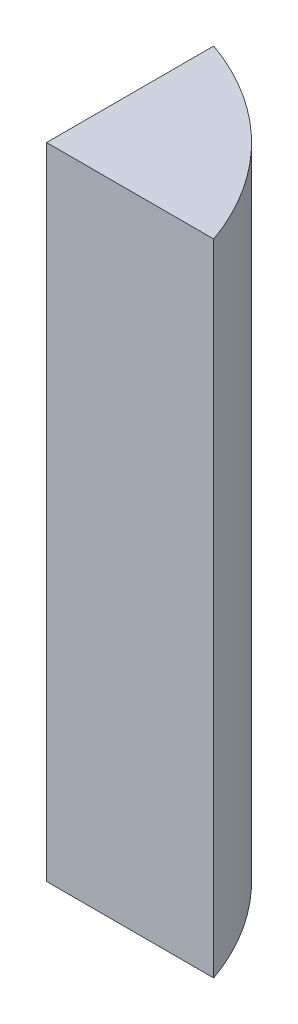
SolidWorks part; units mm, degrees
ref_plane "前视基准面" through (0, 0, 0) normal (0, 0, 1) x (1, 0, 0)
ref_plane "上视基准面" through (0, 0, 0) normal (0, 1, 0) x (1, 0, 0)
ref_plane "右视基准面" through (0, 0, 0) normal (1, 0, 0) x (0, 0, -1)
sketch "草图1" plane through (0, 0, 0) normal (0, 1, 0) x (1, 0, 0)
  line L0 (-56.5685, -20) -> (56.5685, -20)
  line L1 (-56.5685, 20) -> (56.5685, 20)
  line L2 (-20, 56.5685) -> (-20, -56.5685)
  line L3 (20, 56.5685) -> (20, -56.5685)
  circle A0 centre (0, 0) radius 60
  dimension "D1" = 120
  dimension "D2" = 20
  dimension "D3" = 20
  dimension "D4" = 20
  dimension "D5" = 20
extrude "凸台-拉伸1" add sketch "草图1" along normal blind 140 contours L1 A0 L3
